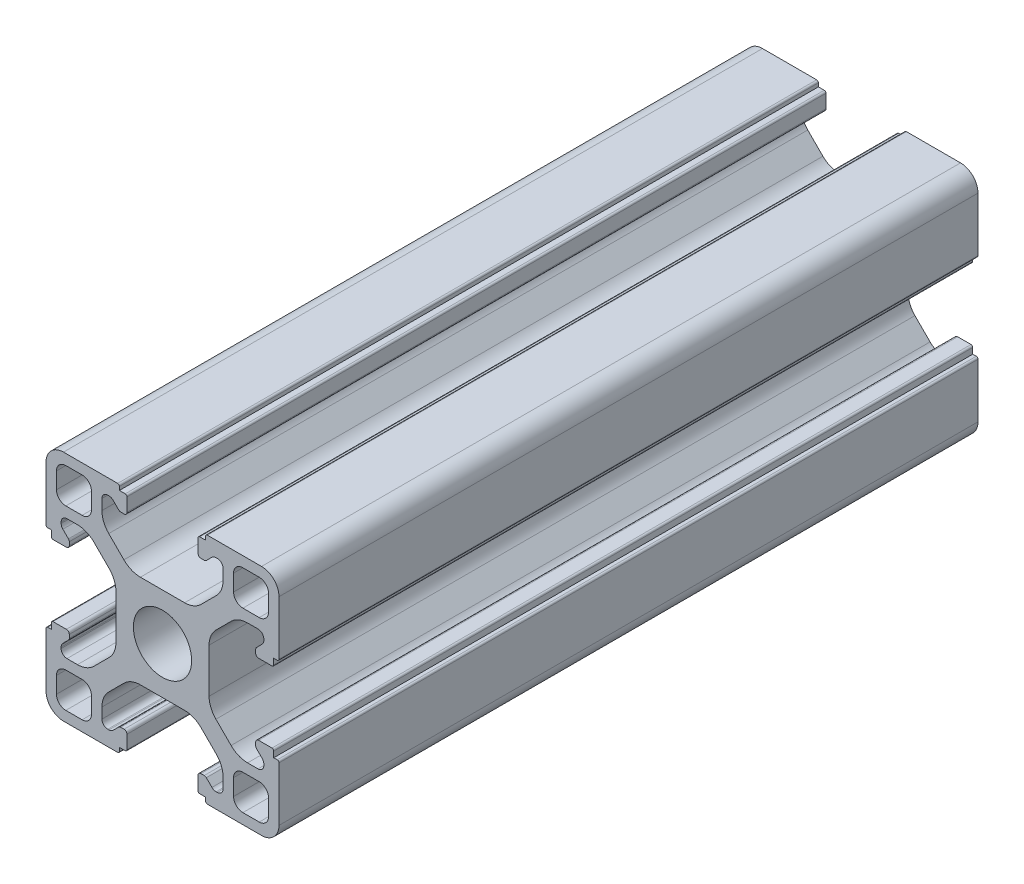
SolidWorks part; units mm, degrees
material "1060 Сплав"
ref_plane "Спереди" through (0, 0, 0) normal (0, 0, 1) x (1, 0, 0)
ref_plane "Сверху" through (0, 0, 0) normal (0, 1, 0) x (1, 0, 0)
ref_plane "Справа" through (0, 0, 0) normal (1, 0, 0) x (0, 0, -1)
sketch "Эскиз1" plane through (0, 0, 0) normal (0, 0, 1) x (1, 0, 0)
  line L0 (9.0997, 9.6536) -> (6.0997, 6.6536) construction
  line L1 (-0.0003, 4.5536) -> (1.8985, 4.5536)
  line L2 (-0.0003, 0.5536) -> (9.9997, 10.5536) construction
  line L3 (7.5997, 8.1536) -> (6.0997, 9.6536) construction
  line L4 (3.3127, 5.1394) -> (4.6139, 6.4406)
  line L5 (6.8997, 6.6536) -> (8.2997, 6.6536)
  line L6 (6.0997, 7.4536) -> (6.0997, 8.8536)
  line L7 (8.2997, 9.6536) -> (6.8997, 9.6536)
  line L8 (5.1997, 8.7536) -> (5.1997, 7.8548)
  line L9 (3.7629, 8.6268) -> (4.2433, 9.1071)
  line L10 (3.1997, 10.1027) -> (3.6997, 10.1027)
  line L11 (3.5862, 8.5536) -> (3.2997, 8.5536)
  line L12 (4.5968, 9.2536) -> (4.6997, 9.2536)
  line L13 (3.6997, 10.4036) -> (3.6997, 10.1027)
  line L14 (3.0497, 9.9527) -> (3.0497, 8.8036)
  line L15 (8.4997, 10.5536) -> (3.8497, 10.5536)
  line L16 (9.0997, 8.8536) -> (9.0997, 7.4536)
  line L17 (9.9997, 9.0536) -> (9.9997, 4.4036)
  line L18 (9.3988, 3.6036) -> (8.2497, 3.6036)
  line L19 (9.8497, 4.2536) -> (9.5488, 4.2536)
  line L20 (8.6997, 5.1507) -> (8.6997, 5.2536)
  line L21 (7.9997, 4.14) -> (7.9997, 3.8536)
  line L22 (9.5488, 3.7536) -> (9.5488, 4.2536)
  line L23 (8.0729, 4.3168) -> (8.5533, 4.7971)
  line L24 (8.1997, 5.7536) -> (7.3009, 5.7536)
  line L25 (4.5855, 3.8666) -> (5.8867, 5.1678)
  line L26 (3.9997, 0.5536) -> (3.9997, 2.4524)
  line L27 (3.9997, 0.5536) -> (3.9997, -1.3452)
  line L28 (4.5855, -2.7594) -> (5.8867, -4.0606)
  line L29 (6.0997, -6.3464) -> (6.0997, -7.7464)
  line L30 (6.8997, -5.5464) -> (8.2997, -5.5464)
  line L31 (9.0997, -7.7464) -> (9.0997, -6.3464)
  line L32 (8.1997, -4.6464) -> (7.3009, -4.6464)
  line L33 (8.0729, -3.2096) -> (8.5533, -3.69)
  line L34 (9.5488, -2.6464) -> (9.5488, -3.1464)
  line L35 (7.9997, -3.0329) -> (7.9997, -2.7464)
  line L36 (8.6997, -4.0435) -> (8.6997, -4.1464)
  line L37 (9.8497, -3.1464) -> (9.5488, -3.1464)
  line L38 (9.3988, -2.4964) -> (8.2497, -2.4964)
  line L39 (9.9997, -7.9464) -> (9.9997, -3.2964)
  line L40 (8.2997, -8.5464) -> (6.8997, -8.5464)
  line L41 (8.4997, -9.4464) -> (3.8497, -9.4464)
  line L42 (3.0497, -8.8455) -> (3.0497, -7.6964)
  line L43 (3.6997, -9.2964) -> (3.6997, -8.9955)
  line L44 (4.5968, -8.1464) -> (4.6997, -8.1464)
  line L45 (3.5862, -7.4464) -> (3.2997, -7.4464)
  line L46 (3.1997, -8.9955) -> (3.6997, -8.9955)
  line L47 (3.7629, -7.5196) -> (4.2433, -8)
  line L48 (5.1997, -7.6464) -> (5.1997, -6.7476)
  line L49 (3.3127, -4.0322) -> (4.6139, -5.3334)
  line L50 (-0.0003, -3.4464) -> (1.8985, -3.4464)
  line L51 (9.0997, -8.5464) -> (6.0997, -5.5464) construction
  line L52 (-0.0003, 0.5536) -> (9.9997, -9.4464) construction
  line L53 (7.5997, -7.0464) -> (9.0997, -5.5464) construction
  line L54 (-0.0003, -3.4464) -> (-1.8991, -3.4464)
  line L55 (-3.3133, -4.0322) -> (-4.6145, -5.3334)
  line L56 (-6.9003, -5.5464) -> (-8.3003, -5.5464)
  line L57 (-6.1003, -6.3464) -> (-6.1003, -7.7464)
  line L58 (-8.3003, -8.5464) -> (-6.9003, -8.5464)
  line L59 (-5.2003, -7.6464) -> (-5.2003, -6.7476)
  line L60 (-3.7635, -7.5196) -> (-4.2438, -8)
  line L61 (-3.2003, -8.9955) -> (-3.7003, -8.9955)
  line L62 (-3.5867, -7.4464) -> (-3.3003, -7.4464)
  line L63 (-4.5974, -8.1464) -> (-4.7003, -8.1464)
  line L64 (-3.7003, -9.2964) -> (-3.7003, -8.9955)
  line L65 (-3.0503, -8.8455) -> (-3.0503, -7.6964)
  line L66 (-8.5003, -9.4464) -> (-3.8503, -9.4464)
  line L67 (-9.1003, -7.7464) -> (-9.1003, -6.3464)
  line L68 (-10.0003, -7.9464) -> (-10.0003, -3.2964)
  line L69 (-9.3994, -2.4964) -> (-8.2503, -2.4964)
  line L70 (-9.8503, -3.1464) -> (-9.5494, -3.1464)
  line L71 (-8.7003, -4.0435) -> (-8.7003, -4.1464)
  line L72 (-8.0003, -3.0329) -> (-8.0003, -2.7464)
  line L73 (-9.5494, -2.6464) -> (-9.5494, -3.1464)
  line L74 (-8.0735, -3.2096) -> (-8.5538, -3.69)
  line L75 (-8.2003, -4.6464) -> (-7.3015, -4.6464)
  line L76 (-4.5861, -2.7594) -> (-5.8873, -4.0606)
  line L77 (-4.0003, 0.5536) -> (-4.0003, -1.3452)
  line L78 (-9.1003, -8.5464) -> (-6.1003, -5.5464) construction
  line L79 (-0.0003, 0.5536) -> (-10.0003, -9.4464) construction
  line L80 (-7.6003, -7.0464) -> (-6.1003, -8.5464) construction
  line L81 (-4.0003, 0.5536) -> (-4.0003, 2.4524)
  line L82 (-4.5861, 3.8666) -> (-5.8873, 5.1678)
  line L83 (-6.1003, 7.4536) -> (-6.1003, 8.8536)
  line L84 (-6.9003, 6.6536) -> (-8.3003, 6.6536)
  line L85 (-9.1003, 8.8536) -> (-9.1003, 7.4536)
  line L86 (-8.2003, 5.7536) -> (-7.3015, 5.7536)
  line L87 (-8.0735, 4.3168) -> (-8.5538, 4.7971)
  line L88 (-9.5494, 3.7536) -> (-9.5494, 4.2536)
  line L89 (-8.0003, 4.14) -> (-8.0003, 3.8536)
  line L90 (-8.7003, 5.1507) -> (-8.7003, 5.2536)
  line L91 (-9.8503, 4.2536) -> (-9.5494, 4.2536)
  line L92 (-9.3994, 3.6036) -> (-8.2503, 3.6036)
  line L93 (-10.0003, 9.0536) -> (-10.0003, 4.4036)
  line L94 (-8.3003, 9.6536) -> (-6.9003, 9.6536)
  line L95 (-8.5003, 10.5536) -> (-3.8503, 10.5536)
  line L96 (-3.0503, 9.9527) -> (-3.0503, 8.8036)
  line L97 (-3.7003, 10.4036) -> (-3.7003, 10.1027)
  line L98 (-4.5974, 9.2536) -> (-4.7003, 9.2536)
  line L99 (-3.5867, 8.5536) -> (-3.3003, 8.5536)
  line L100 (-3.2003, 10.1027) -> (-3.7003, 10.1027)
  line L101 (-3.7635, 8.6268) -> (-4.2438, 9.1071)
  line L102 (-5.2003, 8.7536) -> (-5.2003, 7.8548)
  line L103 (-3.3133, 5.1394) -> (-4.6145, 6.4406)
  line L104 (-0.0003, 4.5536) -> (-1.8991, 4.5536)
  line L105 (-11.7644, 0.5536) -> (11.5041, 0.5536) construction
  line L106 (-9.1003, 9.6536) -> (-6.1003, 6.6536) construction
  line L107 (-0.0003, -11.5328) -> (-0.0003, 11.2725) construction
  line L108 (-0.0003, 0.5536) -> (-10.0003, 10.5536) construction
  line L109 (-7.6003, 8.1536) -> (-9.1003, 6.6536) construction
  arc A0 (9.0997, 8.8536) -> (8.2997, 9.6536) centre (8.2997, 8.8536) ccw
  arc A1 (6.8997, 9.6536) -> (6.0997, 8.8536) centre (6.8997, 8.8536) ccw
  arc A2 (6.8997, 6.6536) -> (6.0997, 7.4536) centre (6.8997, 7.4536) cw
  arc A3 (8.4997, 10.5536) -> (9.9997, 9.0536) centre (8.4997, 9.0536) cw
  arc A4 (3.1997, 10.1027) -> (3.0497, 9.9527) centre (3.1997, 9.9527) ccw
  arc A5 (3.8497, 10.5536) -> (3.6997, 10.4036) centre (3.8497, 10.4036) ccw
  arc A6 (3.5862, 8.5536) -> (3.7629, 8.6268) centre (3.5862, 8.8036) ccw
  arc A7 (3.2997, 8.5536) -> (3.0497, 8.8036) centre (3.2997, 8.8036) cw
  arc A8 (4.2433, 9.1071) -> (4.5968, 9.2536) centre (4.5968, 8.7536) cw
  arc A9 (4.6997, 9.2536) -> (5.1997, 8.7536) centre (4.6997, 8.7536) cw
  arc A10 (2.4997, 0.5536) -> (-0.0003, 3.0536) centre (-0.0003, 0.5536) ccw
  arc A11 (1.8985, 4.5536) -> (3.3127, 5.1394) centre (1.8985, 6.5536) ccw
  arc A12 (5.1997, 7.8548) -> (4.6139, 6.4406) centre (3.1997, 7.8548) cw
  arc A13 (9.0997, 7.4536) -> (8.2997, 6.6536) centre (8.2997, 7.4536) cw
  arc A14 (8.6997, 5.2536) -> (8.1997, 5.7536) centre (8.1997, 5.2536) ccw
  arc A15 (8.5533, 4.7971) -> (8.6997, 5.1507) centre (8.1997, 5.1507) ccw
  arc A16 (7.9997, 3.8536) -> (8.2497, 3.6036) centre (8.2497, 3.8536) ccw
  arc A17 (7.9997, 4.14) -> (8.0729, 4.3168) centre (8.2497, 4.14) cw
  arc A18 (9.9997, 4.4036) -> (9.8497, 4.2536) centre (9.8497, 4.4036) cw
  arc A19 (9.5488, 3.7536) -> (9.3988, 3.6036) centre (9.3988, 3.7536) cw
  arc A20 (7.3009, 5.7536) -> (5.8867, 5.1678) centre (7.3009, 3.7536) ccw
  arc A21 (3.9997, 2.4524) -> (4.5855, 3.8666) centre (5.9997, 2.4524) cw
  arc A22 (8.2997, -8.5464) -> (9.0997, -7.7464) centre (8.2997, -7.7464) ccw
  arc A23 (9.0997, -6.3464) -> (8.2997, -5.5464) centre (8.2997, -6.3464) ccw
  arc A24 (6.0997, -6.3464) -> (6.8997, -5.5464) centre (6.8997, -6.3464) cw
  arc A25 (9.9997, -7.9464) -> (8.4997, -9.4464) centre (8.4997, -7.9464) cw
  arc A26 (9.5488, -2.6464) -> (9.3988, -2.4964) centre (9.3988, -2.6464) ccw
  arc A27 (9.9997, -3.2964) -> (9.8497, -3.1464) centre (9.8497, -3.2964) ccw
  arc A28 (7.9997, -3.0329) -> (8.0729, -3.2096) centre (8.2497, -3.0329) ccw
  arc A29 (7.9997, -2.7464) -> (8.2497, -2.4964) centre (8.2497, -2.7464) cw
  arc A30 (8.5533, -3.69) -> (8.6997, -4.0435) centre (8.1997, -4.0435) cw
  arc A31 (8.6997, -4.1464) -> (8.1997, -4.6464) centre (8.1997, -4.1464) cw
  arc A32 (-0.0003, -1.9464) -> (2.4997, 0.5536) centre (-0.0003, 0.5536) ccw
  arc A33 (3.9997, -1.3452) -> (4.5855, -2.7594) centre (5.9997, -1.3452) ccw
  arc A34 (7.3009, -4.6464) -> (5.8867, -4.0606) centre (7.3009, -2.6464) cw
  arc A35 (6.8997, -8.5464) -> (6.0997, -7.7464) centre (6.8997, -7.7464) cw
  arc A36 (4.6997, -8.1464) -> (5.1997, -7.6464) centre (4.6997, -7.6464) ccw
  arc A37 (4.2433, -8) -> (4.5968, -8.1464) centre (4.5968, -7.6464) ccw
  arc A38 (3.2997, -7.4464) -> (3.0497, -7.6964) centre (3.2997, -7.6964) ccw
  arc A39 (3.5862, -7.4464) -> (3.7629, -7.5196) centre (3.5862, -7.6964) cw
  arc A40 (3.8497, -9.4464) -> (3.6997, -9.2964) centre (3.8497, -9.2964) cw
  arc A41 (3.1997, -8.9955) -> (3.0497, -8.8455) centre (3.1997, -8.8455) cw
  arc A42 (5.1997, -6.7476) -> (4.6139, -5.3334) centre (3.1997, -6.7476) ccw
  arc A43 (1.8985, -3.4464) -> (3.3127, -4.0322) centre (1.8985, -5.4464) cw
  arc A44 (-9.1003, -7.7464) -> (-8.3003, -8.5464) centre (-8.3003, -7.7464) ccw
  arc A45 (-6.9003, -8.5464) -> (-6.1003, -7.7464) centre (-6.9003, -7.7464) ccw
  arc A46 (-6.9003, -5.5464) -> (-6.1003, -6.3464) centre (-6.9003, -6.3464) cw
  arc A47 (-8.5003, -9.4464) -> (-10.0003, -7.9464) centre (-8.5003, -7.9464) cw
  arc A48 (-3.2003, -8.9955) -> (-3.0503, -8.8455) centre (-3.2003, -8.8455) ccw
  arc A49 (-3.8503, -9.4464) -> (-3.7003, -9.2964) centre (-3.8503, -9.2964) ccw
  arc A50 (-3.5867, -7.4464) -> (-3.7635, -7.5196) centre (-3.5867, -7.6964) ccw
  arc A51 (-3.3003, -7.4464) -> (-3.0503, -7.6964) centre (-3.3003, -7.6964) cw
  arc A52 (-4.2438, -8) -> (-4.5974, -8.1464) centre (-4.5974, -7.6464) cw
  arc A53 (-4.7003, -8.1464) -> (-5.2003, -7.6464) centre (-4.7003, -7.6464) cw
  arc A54 (-2.5003, 0.5536) -> (-0.0003, -1.9464) centre (-0.0003, 0.5536) ccw
  arc A55 (-1.8991, -3.4464) -> (-3.3133, -4.0322) centre (-1.8991, -5.4464) ccw
  arc A56 (-5.2003, -6.7476) -> (-4.6145, -5.3334) centre (-3.2003, -6.7476) cw
  arc A57 (-9.1003, -6.3464) -> (-8.3003, -5.5464) centre (-8.3003, -6.3464) cw
  arc A58 (-8.7003, -4.1464) -> (-8.2003, -4.6464) centre (-8.2003, -4.1464) ccw
  arc A59 (-8.5538, -3.69) -> (-8.7003, -4.0435) centre (-8.2003, -4.0435) ccw
  arc A60 (-8.0003, -2.7464) -> (-8.2503, -2.4964) centre (-8.2503, -2.7464) ccw
  arc A61 (-8.0003, -3.0329) -> (-8.0735, -3.2096) centre (-8.2503, -3.0329) cw
  arc A62 (-10.0003, -3.2964) -> (-9.8503, -3.1464) centre (-9.8503, -3.2964) cw
  arc A63 (-9.5494, -2.6464) -> (-9.3994, -2.4964) centre (-9.3994, -2.6464) cw
  arc A64 (-7.3015, -4.6464) -> (-5.8873, -4.0606) centre (-7.3015, -2.6464) ccw
  arc A65 (-4.0003, -1.3452) -> (-4.5861, -2.7594) centre (-6.0003, -1.3452) cw
  arc A66 (-8.3003, 9.6536) -> (-9.1003, 8.8536) centre (-8.3003, 8.8536) ccw
  arc A67 (-9.1003, 7.4536) -> (-8.3003, 6.6536) centre (-8.3003, 7.4536) ccw
  arc A68 (-6.1003, 7.4536) -> (-6.9003, 6.6536) centre (-6.9003, 7.4536) cw
  arc A69 (-10.0003, 9.0536) -> (-8.5003, 10.5536) centre (-8.5003, 9.0536) cw
  arc A70 (-9.5494, 3.7536) -> (-9.3994, 3.6036) centre (-9.3994, 3.7536) ccw
  arc A71 (-10.0003, 4.4036) -> (-9.8503, 4.2536) centre (-9.8503, 4.4036) ccw
  arc A72 (-8.0003, 4.14) -> (-8.0735, 4.3168) centre (-8.2503, 4.14) ccw
  arc A73 (-8.0003, 3.8536) -> (-8.2503, 3.6036) centre (-8.2503, 3.8536) cw
  arc A74 (-8.5538, 4.7971) -> (-8.7003, 5.1507) centre (-8.2003, 5.1507) cw
  arc A75 (-8.7003, 5.2536) -> (-8.2003, 5.7536) centre (-8.2003, 5.2536) cw
  arc A76 (-0.0003, 3.0536) -> (-2.5003, 0.5536) centre (-0.0003, 0.5536) ccw
  arc A77 (-4.0003, 2.4524) -> (-4.5861, 3.8666) centre (-6.0003, 2.4524) ccw
  arc A78 (-7.3015, 5.7536) -> (-5.8873, 5.1678) centre (-7.3015, 3.7536) cw
  arc A79 (-6.9003, 9.6536) -> (-6.1003, 8.8536) centre (-6.9003, 8.8536) cw
  arc A80 (-4.7003, 9.2536) -> (-5.2003, 8.7536) centre (-4.7003, 8.7536) ccw
  arc A81 (-4.2438, 9.1071) -> (-4.5974, 9.2536) centre (-4.5974, 8.7536) ccw
  arc A82 (-3.3003, 8.5536) -> (-3.0503, 8.8036) centre (-3.3003, 8.8036) ccw
  arc A83 (-3.5867, 8.5536) -> (-3.7635, 8.6268) centre (-3.5867, 8.8036) cw
  arc A84 (-3.8503, 10.5536) -> (-3.7003, 10.4036) centre (-3.8503, 10.4036) cw
  arc A85 (-3.2003, 10.1027) -> (-3.0503, 9.9527) centre (-3.2003, 9.9527) cw
  arc A86 (-5.2003, 7.8548) -> (-4.6145, 6.4406) centre (-3.2003, 7.8548) ccw
  arc A87 (-1.8991, 4.5536) -> (-3.3133, 5.1394) centre (-1.8991, 6.5536) cw
  point P0 (-0.0003, 0.5536)
  point P9 (-0.0003, 0.5536)
  point P40 (8.6997, 4.2536)
  point P93 (3.6997, -8.1464)
  point P144 (3.6997, 9.2536)
  point P152 (8.6997, -3.1464)
  point P153 (-0.0003, -3.3707)
  point P154 (-0.0003, 0.5536)
  point P189 (-8.7003, -3.1464)
  point P228 (-3.7003, -8.1464)
  point P229 (-3.9246, 0.5536)
  point P230 (-0.0003, 0.5536)
  point P268 (-3.7003, 9.2536)
  point P273 (3.924, 0.5536)
  point P306 (-8.7003, 4.2536)
  point P307 (-0.0003, 4.4778)
  point P309 (-0.0003, 0.5536)
  dimension "D2" = 5
  dimension "D5" = 2
  dimension "D1" = 6
  dimension "D3" = 4
  dimension "D4" = 0.9
extrude "Бобышка-Вытянуть1" add sketch "Эскиз1" along normal blind 60
